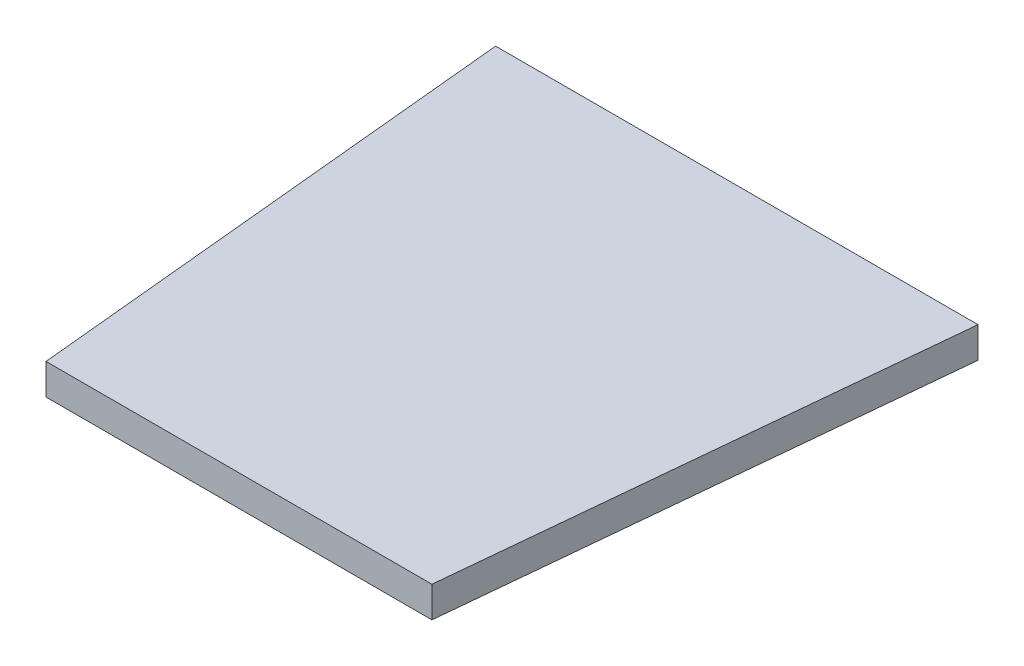
SolidWorks part; units mm, degrees
ref_plane "Front Plane" through (0, 0, 0) normal (0, 0, 1) x (1, 0, 0)
ref_plane "Top Plane" through (0, 0, 0) normal (0, 1, 0) x (1, 0, 0)
ref_plane "Right Plane" through (0, 0, 0) normal (1, 0, 0) x (0, 0, -1)
sketch "Sketch1" plane through (0, 0, 0) normal (0, 1, 0) x (1, 0, 0)
  line L0 (10, -11.9702) -> (-10, -11.9702)
  line L1 (-10, -11.9702) -> (-12.5, 13.8298)
  line L2 (-12.5, 13.8298) -> (12.5, 13.8298)
  line L3 (0, -23.0496) -> (0, 27.305) construction
  line L4 (10, -11.9702) -> (12.5, 13.8298)
  point P8 (0, 13.8298)
  point P9 (0, -11.9702)
  dimension "D1" = 20
  dimension "D2" = 25
  dimension "D3" = 25.8
extrude "Boss-Extrude1" add sketch "Sketch1" along normal blind 1.6
